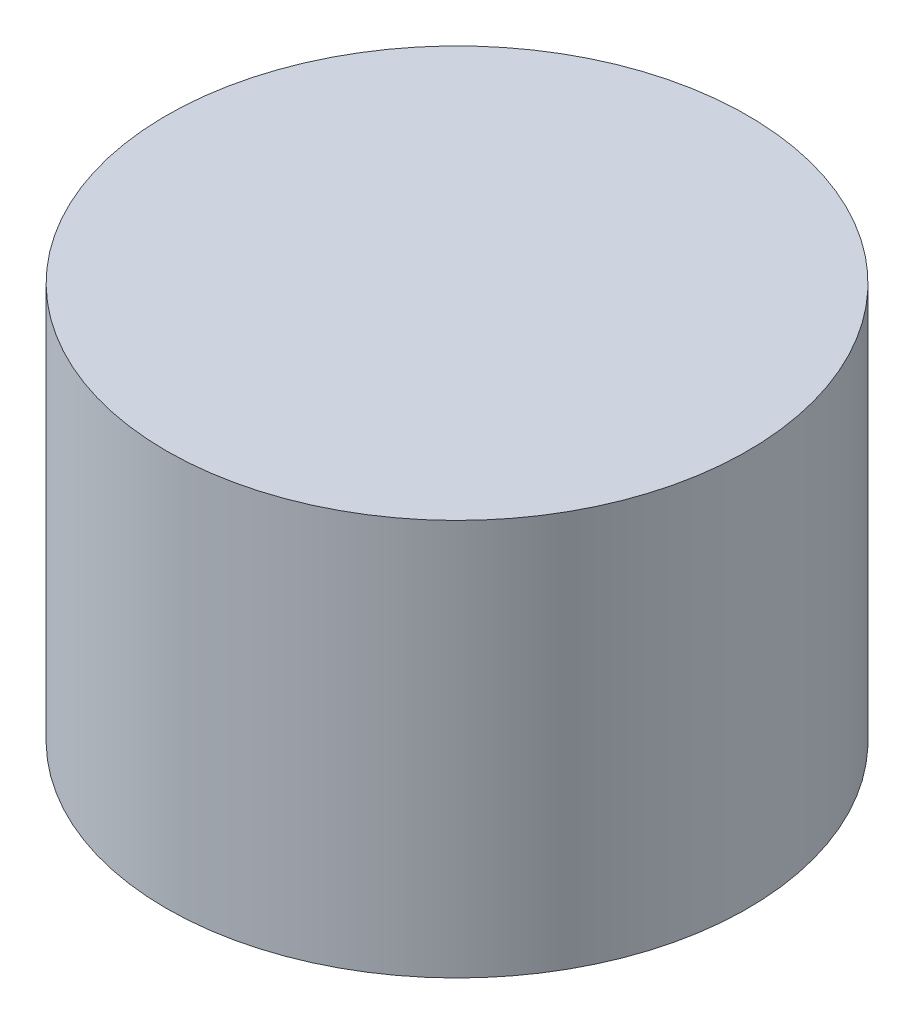
SolidWorks part; units mm, degrees
ref_plane "Front Plane" through (0, 0, 0) normal (0, 0, 1) x (1, 0, 0)
ref_plane "Top Plane" through (0, 0, 0) normal (0, 1, 0) x (1, 0, 0)
ref_plane "Right Plane" through (0, 0, 0) normal (1, 0, 0) x (0, 0, -1)
sketch "Sketch1" plane through (0, 0, 0) normal (0, 1, 0) x (1, 0, 0)
  circle A0 centre (0, 0) radius 1.2
  circle A1 centre (0, 0) radius 2.2
  dimension "D1" = 2.4
  dimension "D2" = 1
extrude "Boss-Extrude1" add sketch "Sketch1" along normal blind 1.5
sketch "Sketch2" plane through (0, 1.5, 0) normal (0, 1, 0) x (1, 0, 0)
  circle A0 centre (0, 0) radius 2.2 construction
  circle A1 centre (0, 0) radius 2.2
extrude "Boss-Extrude2" add sketch "Sketch2" along normal blind 1.5
